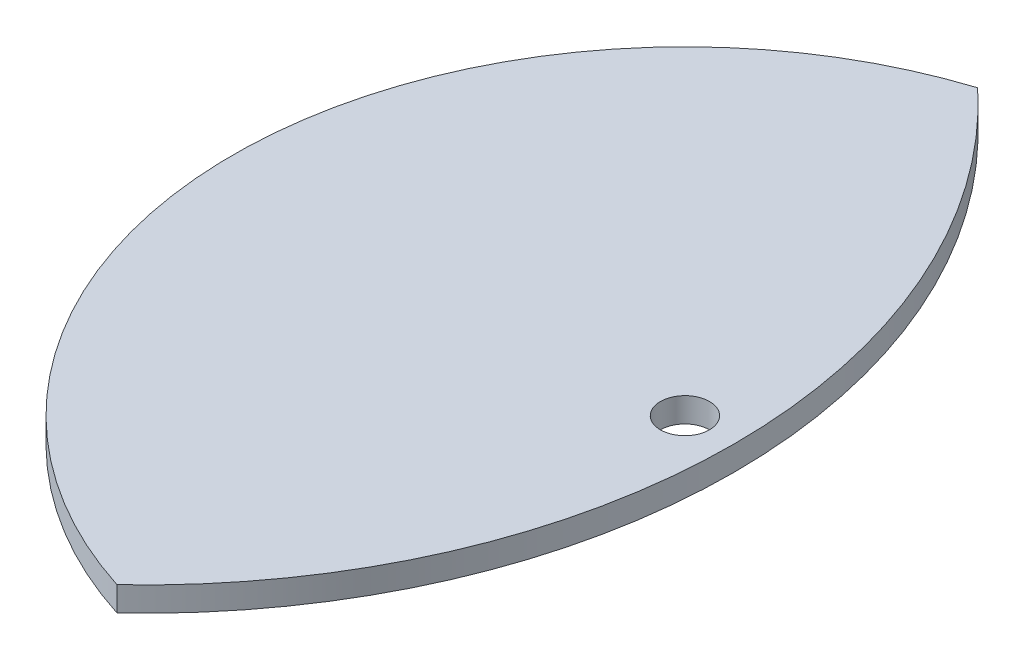
SolidWorks part; units mm, degrees
ref_plane "Front Plane" through (0, 0, 0) normal (0, 0, 1) x (1, 0, 0)
ref_plane "Top Plane" through (0, 0, 0) normal (0, 1, 0) x (1, 0, 0)
ref_plane "Right Plane" through (0, 0, 0) normal (1, 0, 0) x (0, 0, -1)
sketch "Sketch1" plane through (0, 0, 0) normal (0, 1, 0) x (1, 0, 0)
  line L0 (0, 0) -> (76.2, 0) construction
  circle A0 centre (0, 0) radius 76.2 construction
  arc A1 (76.2, 0) -> (52.0585, 55.6449) centre (0, 0) ccw
  arc A2 (52.0585, -55.6449) -> (52.0585, 55.6449) centre (69.85, 0) cw
  circle A3 centre (69.85, 0) radius 3.175
  arc A4 (52.0585, -55.6449) -> (76.2, 0) centre (0, 0) ccw
  point P9 (11.43, 0)
  dimension "D3" = 6.35
  dimension "D1" = 76.2
  dimension "D2" = 6.35
  dimension "D4" = 11.43
extrude "Boss-Extrude1" add sketch "Sketch1" along normal blind 3.175
